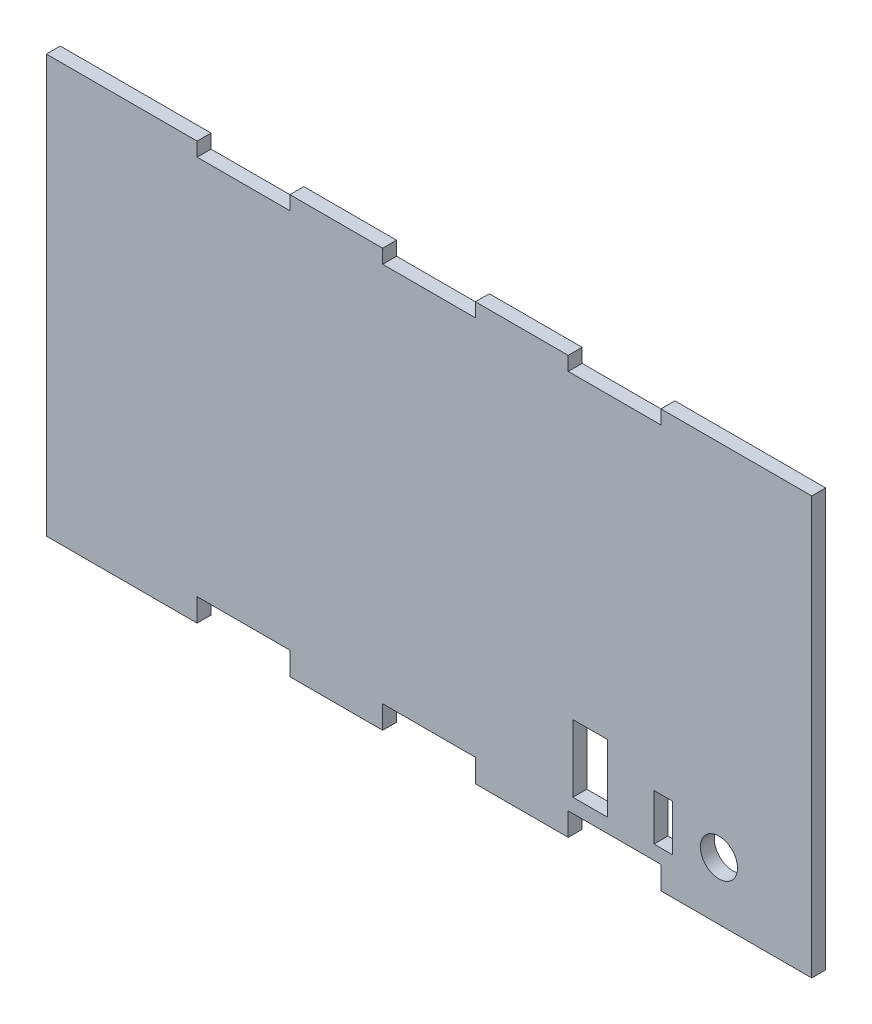
SolidWorks part; units mm, degrees
ref_plane "Plan de face" through (0, 0, 0) normal (0, 0, 1) x (1, 0, 0)
ref_plane "Plan de dessus" through (0, 0, 0) normal (0, 1, 0) x (1, 0, 0)
ref_plane "Plan de droite" through (0, 0, 0) normal (1, 0, 0) x (0, 0, -1)
sketch "Esquisse1" plane through (0, 0, 0) normal (0, 0, 1) x (1, 0, 0)
  line L1 (0, 0) -> (-330, 0)
  line L2 (0, 0) -> (0, 180)
  line L3 (0, 180) -> (-330, 180)
  line L4 (-330, 0) -> (-330, 180)
  dimension "D1" = 180
  dimension "D2" = 330
extrude "Boss.-Extru.1" add sketch "Esquisse1" along normal blind 6
sketch "Esquisse2" plane through (0, 0, 6) normal (0, 0, 1) x (1, 0, 0)
  line L0 (0, 180) -> (-330, 180) construction
  line L1 (-265, 180) -> (-225, 180)
  line L2 (-265, 180) -> (-265, 174)
  line L3 (-265, 174) -> (-225, 174)
  line L4 (-225, 180) -> (-225, 174)
  line L5 (-330, 180) -> (-330, 0) construction
  line L6 (-185, 180) -> (-145, 180)
  line L7 (-185, 180) -> (-185, 174)
  line L8 (-185, 174) -> (-145, 174)
  line L9 (-145, 180) -> (-145, 174)
  line L10 (-105, 180) -> (-65, 180)
  line L11 (-105, 180) -> (-105, 174)
  line L12 (-105, 174) -> (-65, 174)
  line L13 (-65, 180) -> (-65, 174)
  line L15 (-330, 0) -> (0, 0) construction
  line L16 (-265, 0) -> (-225, 0)
  line L17 (-265, 0) -> (-265, 9.9036)
  line L18 (-265, 9.9036) -> (-225, 9.9036)
  line L19 (-225, 0) -> (-225, 9.9036)
  line L21 (-185, 0) -> (-145, 0)
  line L22 (-185, 0) -> (-185, 9.9036)
  line L23 (-185, 9.9036) -> (-145, 9.9036)
  line L24 (-145, 0) -> (-145, 9.9036)
  line L25 (-105, 0) -> (-65, 0)
  line L26 (-105, 0) -> (-105, 9.9036)
  line L27 (-105, 9.9036) -> (-65, 9.9036)
  line L28 (-65, 0) -> (-65, 9.9036)
  dimension "D1" = 40
  dimension "D2" = 40
  dimension "D3" = 40
  dimension "D4" = 40
  dimension "D5" = 40
  dimension "D6" = 65
  dimension "D7" = 6
  dimension "D8" = 6
  dimension "D9" = 6
  dimension "D10" = 40
  dimension "D11" = 40
  dimension "D12" = 40
  dimension "D13" = 40
  dimension "D14" = 40
  dimension "D15" = 65
extrude "Enlèv. mat encoche" cut sketch "Esquisse2" against normal blind 6
sketch "Esquisse3" plane through (0, 0, 6) normal (0, 0, 1) x (1, 0, 0)
  line L0 (-145, 0) -> (-105, 0) construction
  line L1 (-103, 45) -> (-88, 45)
  line L2 (-103, 45) -> (-103, 16)
  line L3 (-103, 16) -> (-88, 16)
  line L4 (-88, 45) -> (-88, 16)
  line L5 (-68, 36) -> (-60, 36)
  line L6 (-68, 36) -> (-68, 16)
  line L7 (-68, 16) -> (-60, 16)
  line L8 (-60, 36) -> (-60, 16)
  line L9 (0, 0) -> (0, 180) construction
  circle A0 centre (-40, 25) radius 8
  dimension "D5" = 16
  dimension "D1" = 29
  dimension "D2" = 15
  dimension "D3" = 20
  dimension "D4" = 8
  dimension "D6" = 16
  dimension "D7" = 16
  dimension "D8" = 20
  dimension "D9" = 25
  dimension "D10" = 20
  dimension "D11" = 40
extrude "Enlèv. mat.-Extru.1" cut sketch "Esquisse3" against normal blind 10
